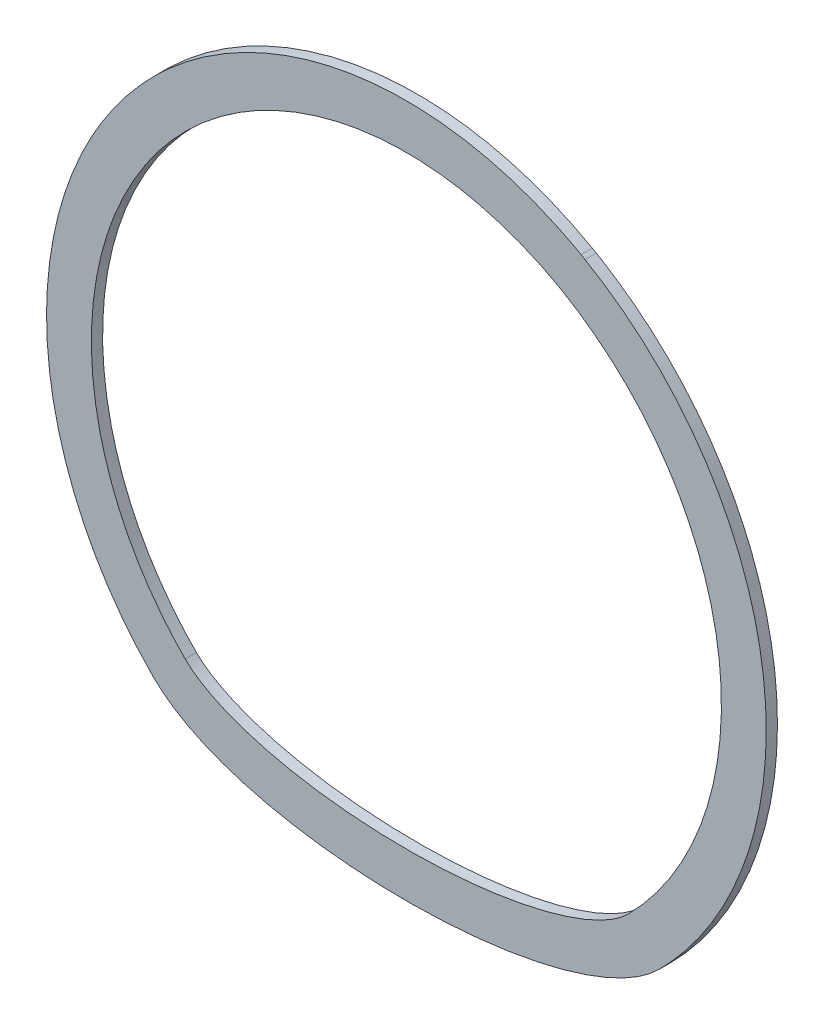
SolidWorks part; units mm, degrees
material "Balsa"
ref_plane "Front Plane" through (0, 0, 0) normal (0, 0, 1) x (1, 0, 0)
ref_plane "Top Plane" through (0, 0, 0) normal (0, 1, 0) x (1, 0, 0)
ref_plane "Right Plane" through (0, 0, 0) normal (1, 0, 0) x (0, 0, -1)
sketch "Sketch2" plane through (0, 0, 0) normal (0, 0, 1) x (1, 0, 0)
  spline S0 degree 3 poles (1287.9624, -2554.2406) (-2426.3955, 2213.412) (3090.079, -1113.4894) (-2871.5436, -21.3318) knots -459.983151 -459.983151 -459.983151 -459.983151 462.568747 462.568747 462.568747 462.568747 only from (49.5009, 91.348) to (50.6103, 90.7129)
  spline S1 degree 3 poles (1979.6046, -2261.5991) (-87.0618, -42.1923) (-53.7983, -91.976) (-74.4696, -70.0026) (-75.8372, -68.488) (-77.1861, -66.9319) (-78.5157, -65.3347) (-79.8244, -63.6962) (-81.5476, -61.4464) (-83.6416, -58.5297) (-85.6296, -55.5014) (-87.1622, -52.9973) (-88.2859, -51.0701) (-90.1147, -47.7724) (-92.5499, -42.8914) (-95.3516, -36.1752) (-97.8068, -28.8548) (-99.4166, -22.4927) (-100.4844, -16.9735) (-101.2174, -12.1158) (-101.8059, -6.1085) (-102.0556, 1.0556) (-101.6376, 11.9166) (-99.5817, 24.7034) (-94.9478, 39.4776) (-88.6565, 52.7081) (-80.0434, 65.5541) (-69.8712, 76.7554) (-58.637, 85.9148) (-47.202, 92.899) (-35.7905, 98.0522) (-24.0008, 101.7167) (-12.0295, 103.8942) (-3.6569, 104.3953) (0.9911, 104.3723) (2.6447, 104.3478) (5.2959, 104.2559) (8.9441, 104.0024) (12.9235, 103.5662) (16.8979, 102.9692) (20.8607, 102.2106) (24.805, 101.2899) (28.7242, 100.207) (32.6113, 98.9619) (36.4593, 97.5551) (39.9429, 96.1186) (42.4433, 94.9816) (43.9946, 94.2376) (44.9225, 93.7809) (45.8466, 93.3143) (46.7667, 92.8378) (47.6827, 92.3514) (67.0215, 81.8398) (128.402, 39.432) (-2600.1329, 1497.4659) knots -0.263593 -0.263593 -0.263593 -0.263593 0.006795 0.013654 0.020575 0.02756 0.034609 0.041722 0.048899 0.063446 0.078252 0.085753 0.09332 0.100952 0.124124 0.148785 0.174948 0.202627 0.215494 0.232144 0.2526 0.276886 0.305032 0.363116 0.408011 0.462235 0.511576 0.564908 0.615598 0.658549 0.700916 0.742691 0.78387 0.82445 0.827809 0.831171 0.841279 0.854802 0.868378 0.882008 0.895692 0.909428 0.923217 0.93706 0.950955 0.964902 0.975398 0.978902 0.982411 0.985922 0.989437 0.992954 0.996476 1.221801 1.221801 1.221801 1.221801 only from (-71.6774, -72.9104) to (49.5009, 91.348)
  spline S2 degree 3 poles (-71.6774, -72.9104) (-72.1092, -72.4767) (-72.9729, -71.5936) (-74.4696, -70.0026) (-75.8372, -68.488) (-77.1861, -66.9319) (-78.5157, -65.3347) (-79.8244, -63.6962) (-81.5476, -61.4464) (-83.6416, -58.5297) (-85.6296, -55.5014) (-87.1622, -52.9973) (-88.2859, -51.0701) (-90.1147, -47.7724) (-92.5499, -42.8914) (-95.3516, -36.1752) (-97.8068, -28.8548) (-99.4166, -22.4927) (-100.4844, -16.9735) (-101.2174, -12.1158) (-101.8059, -6.1085) (-102.0556, 1.0556) (-101.6376, 11.9166) (-99.5817, 24.7034) (-94.9478, 39.4776) (-88.6565, 52.7081) (-80.0434, 65.5541) (-69.8712, 76.7554) (-58.637, 85.9148) (-47.202, 92.899) (-35.7905, 98.0522) (-24.0008, 101.7167) (-12.0295, 103.8942) (-3.6569, 104.3953) (0.9911, 104.3723) (2.6447, 104.3478) (5.2959, 104.2559) (8.9441, 104.0024) (12.9235, 103.5662) (16.8979, 102.9692) (20.8607, 102.2106) (24.805, 101.2899) (28.7242, 100.207) (32.6113, 98.9619) (36.4593, 97.5551) (39.9429, 96.1186) (42.4433, 94.9816) (43.9946, 94.2376) (44.9225, 93.7809) (45.8466, 93.3143) (46.7667, 92.8378) (47.6827, 92.3514) (48.5618, 91.8735) (49.1883, 91.5244) (49.5009, 91.348) knots 0 0 0 0 0.006795 0.013654 0.020575 0.02756 0.034609 0.041722 0.048899 0.063446 0.078252 0.085753 0.09332 0.100952 0.124124 0.148785 0.174948 0.202627 0.215494 0.232144 0.2526 0.276886 0.305032 0.363116 0.408011 0.462235 0.511576 0.564908 0.615598 0.658549 0.700916 0.742691 0.78387 0.82445 0.827809 0.831171 0.841279 0.854802 0.868378 0.882008 0.895692 0.909428 0.923217 0.93706 0.950955 0.964902 0.975398 0.978902 0.982411 0.985922 0.989437 0.992954 0.996476 1 1 1 1
  spline S3 degree 3 poles (49.5009, 91.348) (49.872, 91.1385) (50.2418, 90.9268) (50.6103, 90.7129) knots 0 0 0 0 1 1 1 1
  spline S4 degree 3 poles (-2498.68, 1671.695) (65.809, 68.4783) (27.7489, 104.9071) (53.9325, 88.7036) (55.5798, 87.6387) (57.2181, 86.5331) (58.847, 85.3874) (60.4652, 84.2011) (62.6149, 82.559) (65.2687, 80.4032) (68.3802, 77.661) (71.4204, 74.7537) (74.3792, 71.6812) (77.2464, 68.4441) (79.5428, 65.6199) (81.3243, 63.2803) (82.6352, 61.4798) (83.9151, 59.6395) (85.6826, 56.9767) (87.8969, 53.3695) (90.4626, 48.6769) (92.8892, 43.6261) (95.1327, 38.2157) (97.1465, 32.4482) (98.8821, 26.3306) (100.2892, 19.8751) (101.2586, 13.4739) (101.8173, 7.2467) (102.0152, 1.305) (101.8786, -4.6242) (101.3926, -10.7347) (100.5371, -16.8676) (99.3294, -22.8638) (97.8936, -28.3722) (96.657, -32.2698) (95.7856, -34.7444) (95.046, -36.7643) (93.9532, -39.5358) (92.4358, -43.007) (90.8217, -46.3649) (89.1186, -49.6082) (87.3342, -52.7363) (85.4757, -55.7486) (83.5505, -58.6453) (81.5655, -61.4266) (79.3077, -64.3807) (77.437, -66.6472) (76.0073, -68.2889) (75.2951, -69.0897) (74.579, -69.8782) (73.8594, -70.6545) (73.1363, -71.4184) (61.1769, -83.7796) (103.8516, -35.6847) (-2010.1872, -2232.2253) knots -0.424766 -0.424766 -0.424766 -0.424766 0.010157 0.020393 0.030709 0.041103 0.051576 0.062128 0.072758 0.094254 0.116062 0.138181 0.16061 0.183347 0.206391 0.218027 0.22974 0.241529 0.253393 0.280162 0.30828 0.337739 0.36853 0.400644 0.434071 0.4688 0.504821 0.536145 0.567394 0.59857 0.62967 0.664059 0.696204 0.726123 0.75383 0.760691 0.767516 0.787768 0.807688 0.827278 0.84654 0.865477 0.884089 0.902378 0.920346 0.937994 0.961032 0.966703 0.97234 0.977942 0.983508 0.98904 0.994538 1.224375 1.224375 1.224375 1.224375 only from (50.6103, 90.7129) to (71.6784, -72.9104)
  spline S5 degree 3 poles (50.6103, 90.7129) (51.1284, 90.4118) (52.1672, 89.796) (53.9325, 88.7036) (55.5798, 87.6387) (57.2181, 86.5331) (58.847, 85.3874) (60.4652, 84.2011) (62.6149, 82.559) (65.2687, 80.4032) (68.3802, 77.661) (71.4204, 74.7537) (74.3792, 71.6812) (77.2464, 68.4441) (79.5428, 65.6199) (81.3243, 63.2803) (82.6352, 61.4798) (83.9151, 59.6395) (85.6826, 56.9767) (87.8969, 53.3695) (90.4626, 48.6769) (92.8892, 43.6261) (95.1327, 38.2157) (97.1465, 32.4482) (98.8821, 26.3306) (100.2892, 19.8751) (101.2586, 13.4739) (101.8173, 7.2467) (102.0152, 1.305) (101.8786, -4.6242) (101.3926, -10.7347) (100.5371, -16.8676) (99.3294, -22.8638) (97.8936, -28.3722) (96.657, -32.2698) (95.7856, -34.7444) (95.046, -36.7643) (93.9532, -39.5358) (92.4358, -43.007) (90.8217, -46.3649) (89.1186, -49.6082) (87.3342, -52.7363) (85.4757, -55.7486) (83.5505, -58.6453) (81.5655, -61.4266) (79.3077, -64.3807) (77.437, -66.6472) (76.0073, -68.2889) (75.2951, -69.0897) (74.579, -69.8782) (73.8594, -70.6545) (73.1363, -71.4184) (72.3175, -72.2647) (71.8912, -72.6967) (71.6784, -72.9104) knots 0 0 0 0 0.010157 0.020393 0.030709 0.041103 0.051576 0.062128 0.072758 0.094254 0.116062 0.138181 0.16061 0.183347 0.206391 0.218027 0.22974 0.241529 0.253393 0.280162 0.30828 0.337739 0.36853 0.400644 0.434071 0.4688 0.504821 0.536145 0.567394 0.59857 0.62967 0.664059 0.696204 0.726123 0.75383 0.760691 0.767516 0.787768 0.807688 0.827278 0.84654 0.865477 0.884089 0.902378 0.920346 0.937994 0.961032 0.966703 0.97234 0.977942 0.983508 0.98904 0.994538 1 1 1 1
  spline S6 degree 3 poles (-2851.1816, 560.1676) (3541.403, -309.3697) (-3541.4197, -309.3677) (2851.2262, 560.1735) knots -2.423676 -2.423676 -2.423676 -2.423676 3.42369 3.42369 3.42369 3.42369 weights 1 1 1 1 only from (71.6784, -72.9104) to (-71.6774, -72.9104)
  spline S7 degree 3 poles (71.6784, -72.9104) (46.3599, -98.3417) (-46.3589, -98.3417) (-71.6774, -72.9104) knots 0 0 0 0 1 1 1 1 weights 1 1 1 1
  spline S8 degree 1 poles (-62.6772, -63.9502) (43.2582, 80.2883) knots 0 0 1 1 construction
  spline S9 degree 1 poles (43.2582, 80.2883) (44.2327, 79.7303) knots 0 0 1 1 construction
  spline S10 degree 1 poles (44.2327, 79.7303) (62.6782, -63.9502) knots 0 0 1 1 construction
  spline S11 degree 1 poles (62.6782, -63.9502) (-62.6772, -63.9502) knots 0 0 1 1 construction
  spline S12 degree 3 poles (-62.6772, -63.9502) (-62.8955, -63.7309) (-63.3217, -63.2983) (-64.0021, -62.5921) (-64.7538, -61.7946) (-65.7039, -60.7646) (-66.8046, -59.5274) (-68.5568, -57.4681) (-70.6482, -54.8355) (-73.8114, -50.469) (-77.3945, -44.7561) (-82.3029, -35.1354) (-86.8108, -22.36) (-90.3543, -0.9674) (-87.6499, 26.3501) (-73.3334, 55.9721) (-49.624, 78.7088) (-24.4872, 89.3835) (-3.091, 92.1159) (13.039, 91.1975) (26.1203, 87.9966) (34.8794, 84.5248) (39.1021, 82.5104) (41.2143, 81.4108) (42.347, 80.7976) (42.9592, 80.4569) (43.2582, 80.2883) knots 0 0 0 0 0.003906 0.007812 0.011719 0.015625 0.023437 0.03125 0.046875 0.062499 0.093749 0.124999 0.187498 0.249998 0.374997 0.499996 0.624995 0.749994 0.812493 0.874993 0.937492 0.968742 0.984367 0.992179 0.996085 0.999992 0.999992 0.999992 0.999992
  spline S13 degree 3 poles (43.2582, 80.2883) (43.3397, 80.2423) (43.5025, 80.15) (43.7464, 80.0108) (43.9898, 79.871) (44.1518, 79.7773) (44.2327, 79.7303) knots 0.002022 0.002022 0.002022 0.002022 0.251014 0.500005 0.748996 0.997987 0.997987 0.997987 0.997987
  spline S14 degree 3 poles (44.2327, 79.7303) (44.5844, 79.526) (45.2596, 79.1276) (46.4154, 78.4223) (47.5738, 77.6928) (49.0079, 76.7584) (50.8048, 75.5306) (53.6072, 73.4932) (57.0034, 70.7903) (64.7641, 63.8421) (74.8536, 51.7693) (84.3118, 33.0007) (89.3026, 12.5818) (89.5941, -8.4639) (85.1673, -29.0225) (78.4712, -43.2887) (72.7378, -52.0045) (70.1455, -55.4923) (67.9548, -58.1887) (66.5372, -59.8344) (65.3768, -61.1241) (64.6361, -61.9238) (64.0489, -62.544) (63.5408, -63.0721) (63.0657, -63.5594) (62.8132, -63.8146) (62.6782, -63.9502) knots 0.000015 0.000015 0.000015 0.000015 0.007827 0.015639 0.023452 0.031264 0.046889 0.062514 0.093763 0.125013 0.250011 0.375009 0.500007 0.625005 0.750004 0.875002 0.906251 0.937501 0.953126 0.96875 0.976563 0.984375 0.988281 0.992188 0.996094 1 1 1 1
  spline S15 degree 3 poles (62.6782, -63.9502) (62.4421, -64.1873) (61.9735, -64.6322) (60.8483, -65.5949) (59.1789, -66.8259) (56.7375, -68.3252) (52.9423, -70.2888) (47.261, -72.5995) (39.2215, -74.978) (30.229, -76.8801) (17.3048, -78.7217) (0.0005, -79.6587) (-17.3038, -78.7217) (-30.228, -76.8801) (-39.2204, -74.978) (-47.2599, -72.5995) (-52.9413, -70.2888) (-56.7364, -68.3252) (-59.1779, -66.8259) (-60.8473, -65.5949) (-61.9724, -64.6322) (-62.4411, -64.1873) (-62.6772, -63.9502) knots 0 0 0 0 0.015625 0.03125 0.0625 0.09375 0.125 0.1875 0.25 0.3125 0.375 0.5 0.625 0.6875 0.75 0.8125 0.875 0.90625 0.9375 0.96875 0.984375 1 1 1 1
  dimension "D1" = 12.7
extrude "Boss-Extrude1" add sketch "Sketch2" against normal blind 3.175
